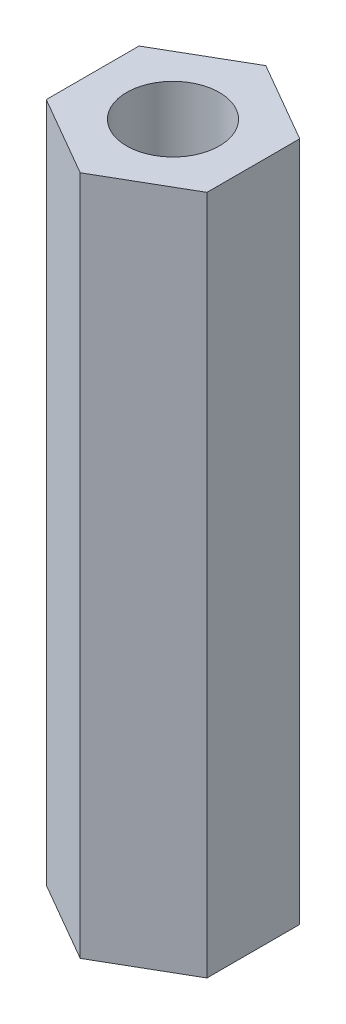
SolidWorks part; units mm, degrees
ref_plane "Спереди" through (0, 0, 0) normal (0, 0, 1) x (1, 0, 0)
ref_plane "Сверху" through (0, 0, 0) normal (0, 1, 0) x (1, 0, 0)
ref_plane "Справа" through (0, 0, 0) normal (1, 0, 0) x (0, 0, -1)
other "Configuration Table"
sketch "Эскиз1" plane through (0, 0, 0) normal (0, 1, 0) x (1, 0, 0)
  line L3 (2.5981, 1.5) -> (0, 3)
  line L4 (-2.5981, 1.5) -> (0, 3)
  line L5 (-2.5981, 1.5) -> (-2.5981, -1.5)
  line L6 (2.5981, 1.5) -> (2.5981, -1.5)
  line L7 (-2.5981, -1.5) -> (0, -3)
  line L8 (0, -3) -> (2.5981, -1.5)
  circle A1 centre (0, 0) radius 3
  circle A6 centre (0, 0) radius 1.5
extrude "Бобышка-Вытянуть1" add sketch "Эскиз1" along normal blind 22 contours L7 L8 L6 L3 L4 L5 A6
